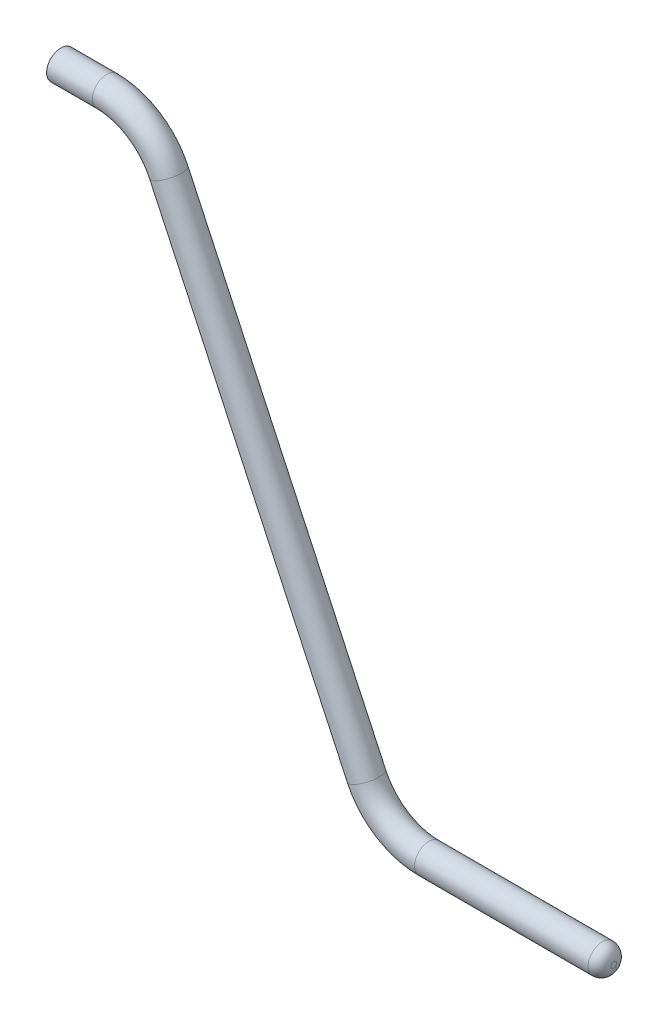
SolidWorks part; units mm, degrees
ref_plane "Front" through (0, 0, 0) normal (0, 0, 1) x (1, 0, 0)
ref_plane "Top" through (0, 0, 0) normal (0, 1, 0) x (1, 0, 0)
ref_plane "Right" through (0, 0, 0) normal (1, 0, 0) x (0, 0, -1)
sketch "Sketch1" plane through (0, 0, 0) normal (0, 0, 1) x (1, 0, 0)
  line L0 (0, 0) -> (-8.0888, 0)
  line L1 (50, 0) -> (-50, 0) construction
  line L2 (-10.8077, 1.7321) -> (-19.4511, 20.2679)
  line L3 (0, -50) -> (0, 50) construction
  line L5 (-24.17, 22) -> (-22.17, 22)
  arc A1 (-8.0888, 0) -> (-10.8077, 1.7321) centre (-8.0888, 3) cw
  arc A2 (-22.17, 22) -> (-19.4511, 20.2679) centre (-22.17, 19) cw
  point P11 (-10, 0)
  dimension "D2" = 25
  dimension "D3" = 3
  dimension "D1" = 10
  dimension "D5" = 22
  dimension "D6" = 2
sketch "Sketch2" plane through (0, 0, 0) normal (1, 0, 0) x (0, 0, -1)
  circle A0 centre (0, 0) radius 0.625
  dimension "D1" = 1.25
sweep "Sweep1" add profiles "Sketch2" path "Sketch1"
fillet "Fillet2" radius 0.5 1 edges at (0, 0, -0.625)
sketch "Sketch3" plane through (-24.17, 0, 0) normal (-1, 0, 0) x (0, 0, 1)
  line L0 (0, 22) -> (0, 23.2851) construction
  circle A0 centre (-0.325, 22) radius 0.3
  circle A1 centre (0.325, 22) radius 0.3
  circle A2 centre (0, 22) radius 0.625 construction
  dimension "D1" = 0.6
extrude "Boss-Extrude2" [suppressed] add sketch "Sketch3" along normal blind 75
